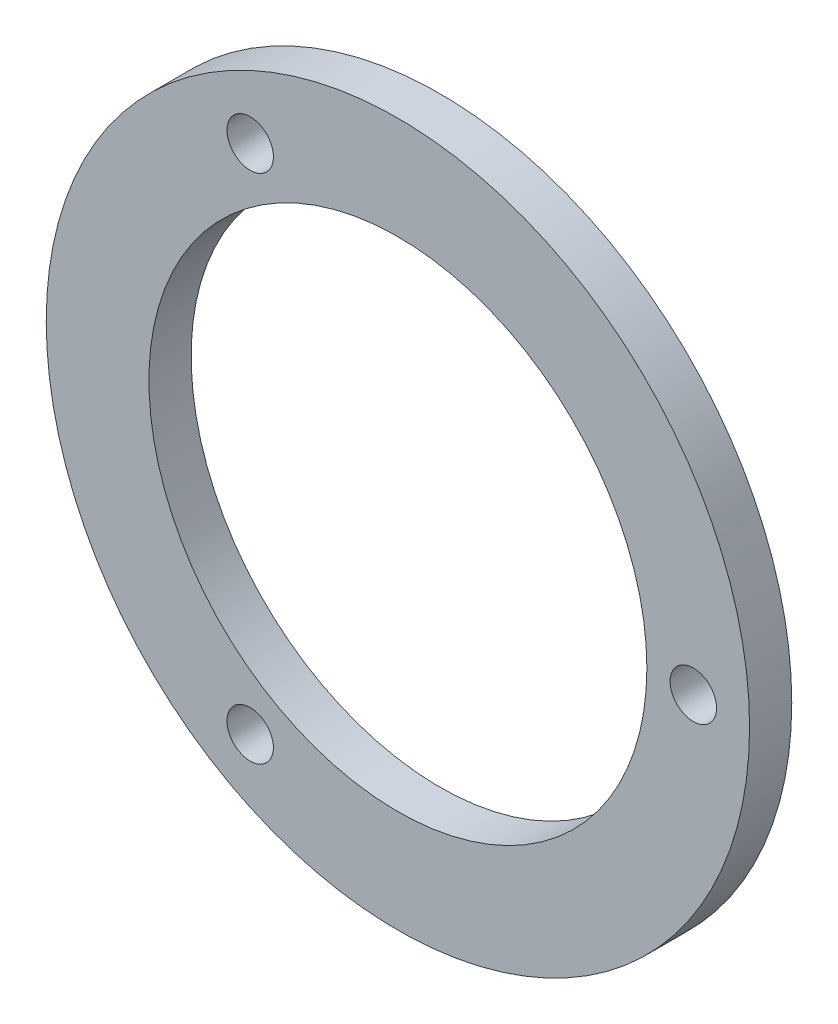
SolidWorks part; units mm, degrees
ref_plane "前视基准面" through (0, 0, 0) normal (0, 0, 1) x (1, 0, 0)
ref_plane "上视基准面" through (0, 0, 0) normal (0, 1, 0) x (1, 0, 0)
ref_plane "右视基准面" through (0, 0, 0) normal (1, 0, 0) x (0, 0, -1)
sketch "草图1" plane through (0, 0, 0) normal (0, 0, 1) x (1, 0, 0)
  line L0 (0, 0) -> (-10.5, 18.1865)
  line L1 (0, 0) -> (-10.5, -18.1865)
  circle A0 centre (0, 0) radius 17.7
  circle A1 centre (0, 0) radius 25
  circle A3 centre (21, 0) radius 1.65
  circle A4 centre (-10.5, 18.1865) radius 1.65
  circle A5 centre (-10.5, -18.1865) radius 1.65
extrude "凸台-拉伸1" add sketch "草图1" along normal blind 3
